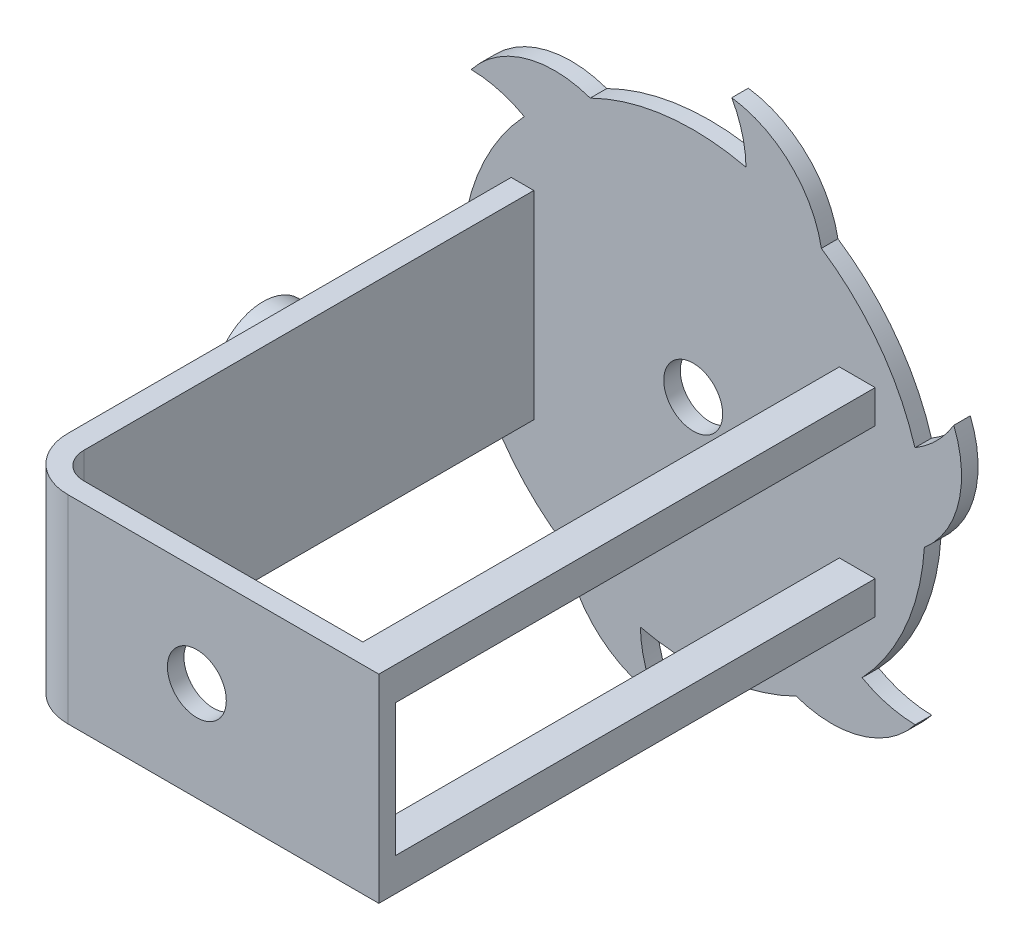
SolidWorks part; units mm, degrees
ref_plane "Front Plane" through (0, 0, 0) normal (0, 0, 1) x (1, 0, 0)
ref_plane "Top Plane" through (0, 0, 0) normal (0, 1, 0) x (1, 0, 0)
ref_plane "Right Plane" through (0, 0, 0) normal (1, 0, 0) x (0, 0, -1)
sketch "Sketch1" plane through (0, 0, 0) normal (0, 0, 1) x (1, 0, 0)
  line L0 (-873.9292, 0) -> (-35, 0) construction
  line L7 (0, -873.9292) -> (0, -35) construction
  line L8 (-618.4754, -618.4754) -> (-24.7487, -24.7487) construction
  line L9 (694.9078, -719.0993) -> (23.7269, -25.73) construction
  line L16 (0, 35) -> (0, 42822.5309) construction
  line L18 (35, 0) -> (42822.5309, 0) construction
  line L19 (-24.945, 24.5509) -> (-34080.9346, 35206.39) construction
  line L21 (24.7487, 24.7487) -> (30279.5878, 30279.5878) construction
  circle A0 centre (0, 0) radius 42.5 construction
  arc A1 (39.3732, 16) -> (33.5028, 10.1274) centre (24.779, 24.7184) cw
  arc A3 (39.3732, 16) -> (34.9308, -2.1991) centre (24.5504, 9.9765) cw
  arc A6 (33.543, -26.0982) -> (15.5609, -31.3506) centre (20.9151, -16.273) cw
  arc A7 (33.543, -26.0982) -> (25.522, -23.9505) centre (33.7963, -9.1001) cw
  arc A10 (-5.8302, -42.0982) -> (-19.3699, -29.1514) centre (-3.6353, -26.2495) cw
  arc A11 (-5.8302, -42.0982) -> (-7.9808, -34.078) centre (9.0172, -33.8185) cw
  arc A14 (-39.3732, -16) -> (-34.9308, 2.1991) centre (-24.5504, -9.9765) cw
  arc A15 (-39.3732, -16) -> (-33.5028, -10.1274) centre (-24.779, -24.7184) cw
  arc A18 (-33.543, 26.0982) -> (-15.5609, 31.3506) centre (-20.9151, 16.273) cw
  arc A19 (-33.543, 26.0982) -> (-25.522, 23.9505) centre (-33.7963, 9.1001) cw
  arc A22 (5.8302, 42.0982) -> (19.3699, 29.1514) centre (3.6353, 26.2495) cw
  arc A23 (5.8302, 42.0982) -> (7.9808, 34.078) centre (-9.0172, 33.8185) cw
  circle A25 centre (0, 0) radius 35
  point P16 (0, 0)
  point P73 (0, 0)
  dimension "D1" = 85
  dimension "D2" = 70
  dimension "D8" = 17
  dimension "D10" = 16
  dimension "D9" = 16
  dimension "D13" = 6
extrude "Boss-Extrude1" add sketch "Sketch1" along normal blind 2.5 contours A25 A14 A15 | A25 | A25 A18 A19 | A25 A22 A23 | A25 A3 A1 | A25 A6 A7 | A25 A10 A11
sketch "Sketch11" plane through (0, 0, 2.5) normal (0, 0, 1) x (1, 0, 0)
  circle A0 centre (0, 0) radius 4.45
  arc A18 (-33.5028, -10.1274) -> (-39.3732, -16) centre (-24.779, -24.7184) ccw
  arc A19 (-33.5028, -10.1274) -> (-19.3699, -29.1514) centre (0, 0) ccw
  arc A20 (-19.3699, -29.1514) -> (-5.8302, -42.0982) centre (-3.6353, -26.2495) ccw
  arc A21 (-7.9808, -34.078) -> (-5.8302, -42.0982) centre (9.0172, -33.8185) ccw
  arc A22 (-7.9808, -34.078) -> (15.5609, -31.3506) centre (0, 0) ccw
  arc A23 (15.5609, -31.3506) -> (33.543, -26.0982) centre (20.9151, -16.273) ccw
  arc A24 (25.522, -23.9505) -> (33.543, -26.0982) centre (33.7963, -9.1001) ccw
  arc A25 (25.522, -23.9505) -> (34.9308, -2.1991) centre (0, 0) ccw
  arc A26 (34.9308, -2.1991) -> (39.3732, 16) centre (24.5504, 9.9765) ccw
  arc A27 (33.5028, 10.1274) -> (39.3732, 16) centre (24.779, 24.7184) ccw
  arc A28 (33.5028, 10.1274) -> (19.3699, 29.1514) centre (0, 0) ccw
  arc A29 (19.3699, 29.1514) -> (5.8302, 42.0982) centre (3.6353, 26.2495) ccw
  arc A30 (7.9808, 34.078) -> (5.8302, 42.0982) centre (-9.0172, 33.8185) ccw
  arc A31 (7.9808, 34.078) -> (-15.5609, 31.3506) centre (0, 0) ccw
  arc A32 (-15.5609, 31.3506) -> (-33.543, 26.0982) centre (-20.9151, 16.273) ccw
  arc A33 (-25.522, 23.9505) -> (-33.543, 26.0982) centre (-33.7963, 9.1001) ccw
  arc A34 (-25.522, 23.9505) -> (-34.9308, 2.1991) centre (0, 0) ccw
  arc A35 (-34.9308, 2.1991) -> (-39.3732, -16) centre (-24.5504, -9.9765) ccw
  arc A36 (-33.5028, -10.1274) -> (-39.3732, -16) centre (-24.779, -24.7184) ccw
  arc A37 (-33.5028, -10.1274) -> (-19.3699, -29.1514) centre (0, 0) ccw
  arc A38 (-19.3699, -29.1514) -> (-5.8302, -42.0982) centre (-3.6353, -26.2495) ccw
  arc A39 (-7.9808, -34.078) -> (-5.8302, -42.0982) centre (9.0172, -33.8185) ccw
  arc A40 (-7.9808, -34.078) -> (15.5609, -31.3506) centre (0, 0) ccw
  arc A41 (15.5609, -31.3506) -> (33.543, -26.0982) centre (20.9151, -16.273) ccw
  arc A42 (25.522, -23.9505) -> (33.543, -26.0982) centre (33.7963, -9.1001) ccw
  arc A43 (25.522, -23.9505) -> (34.9308, -2.1991) centre (0, 0) ccw
  arc A44 (34.9308, -2.1991) -> (39.3732, 16) centre (24.5504, 9.9765) ccw
  arc A45 (33.5028, 10.1274) -> (39.3732, 16) centre (24.779, 24.7184) ccw
  arc A46 (33.5028, 10.1274) -> (19.3699, 29.1514) centre (0, 0) ccw
  arc A47 (19.3699, 29.1514) -> (5.8302, 42.0982) centre (3.6353, 26.2495) ccw
  arc A48 (7.9808, 34.078) -> (5.8302, 42.0982) centre (-9.0172, 33.8185) ccw
  arc A49 (7.9808, 34.078) -> (-15.5609, 31.3506) centre (0, 0) ccw
  arc A50 (-15.5609, 31.3506) -> (-33.543, 26.0982) centre (-20.9151, 16.273) ccw
  arc A51 (-25.522, 23.9505) -> (-33.543, 26.0982) centre (-33.7963, 9.1001) ccw
  arc A52 (-25.522, 23.9505) -> (-34.9308, 2.1991) centre (0, 0) ccw
  arc A53 (-34.9308, 2.1991) -> (-39.3732, -16) centre (-24.5504, -9.9765) ccw
  dimension "D2" = 8.9
  dimension "D1" = 0
extrude "Cut-Extrude5" cut sketch "Sketch11" against normal blind 10 contours A0
sketch "Sketch5" plane through (0, 0, 2.5) normal (0, 0, 1) x (1, 0, 0)
  line L1 (27.5, -15) -> (-27.5, -15)
  line L2 (27.5, -15) -> (27.5, 15)
  line L3 (27.5, 15) -> (-27.5, 15)
  line L4 (-27.5, -15) -> (-27.5, 15)
  line L5 (27.5, -15) -> (-27.5, 15) construction
  line L6 (27.5, 15) -> (-27.5, -15) construction
  arc A18 (-33.5028, -10.1274) -> (-39.3732, -16) centre (-24.779, -24.7184) ccw
  arc A19 (-33.5028, -10.1274) -> (-19.3699, -29.1514) centre (0, 0) ccw
  arc A20 (-19.3699, -29.1514) -> (-5.8302, -42.0982) centre (-3.6353, -26.2495) ccw
  arc A21 (-7.9808, -34.078) -> (-5.8302, -42.0982) centre (9.0172, -33.8185) ccw
  arc A22 (-7.9808, -34.078) -> (15.5609, -31.3506) centre (0, 0) ccw
  arc A23 (15.5609, -31.3506) -> (33.543, -26.0982) centre (20.9151, -16.273) ccw
  arc A24 (25.522, -23.9505) -> (33.543, -26.0982) centre (33.7963, -9.1001) ccw
  arc A25 (25.522, -23.9505) -> (34.9308, -2.1991) centre (0, 0) ccw
  arc A26 (34.9308, -2.1991) -> (39.3732, 16) centre (24.5504, 9.9765) ccw
  arc A27 (33.5028, 10.1274) -> (39.3732, 16) centre (24.779, 24.7184) ccw
  arc A28 (33.5028, 10.1274) -> (19.3699, 29.1514) centre (0, 0) ccw
  arc A29 (19.3699, 29.1514) -> (5.8302, 42.0982) centre (3.6353, 26.2495) ccw
  arc A30 (7.9808, 34.078) -> (5.8302, 42.0982) centre (-9.0172, 33.8185) ccw
  arc A31 (7.9808, 34.078) -> (-15.5609, 31.3506) centre (0, 0) ccw
  arc A32 (-15.5609, 31.3506) -> (-33.543, 26.0982) centre (-20.9151, 16.273) ccw
  arc A33 (-25.522, 23.9505) -> (-33.543, 26.0982) centre (-33.7963, 9.1001) ccw
  arc A34 (-25.522, 23.9505) -> (-34.9308, 2.1991) centre (0, 0) ccw
  arc A35 (-34.9308, 2.1991) -> (-39.3732, -16) centre (-24.5504, -9.9765) ccw
  arc A36 (-33.5028, -10.1274) -> (-39.3732, -16) centre (-24.779, -24.7184) ccw
  arc A37 (-33.5028, -10.1274) -> (-19.3699, -29.1514) centre (0, 0) ccw
  arc A38 (-19.3699, -29.1514) -> (-5.8302, -42.0982) centre (-3.6353, -26.2495) ccw
  arc A39 (-7.9808, -34.078) -> (-5.8302, -42.0982) centre (9.0172, -33.8185) ccw
  arc A40 (-7.9808, -34.078) -> (15.5609, -31.3506) centre (0, 0) ccw
  arc A41 (15.5609, -31.3506) -> (33.543, -26.0982) centre (20.9151, -16.273) ccw
  arc A42 (25.522, -23.9505) -> (33.543, -26.0982) centre (33.7963, -9.1001) ccw
  arc A43 (25.522, -23.9505) -> (34.9308, -2.1991) centre (0, 0) ccw
  arc A44 (34.9308, -2.1991) -> (39.3732, 16) centre (24.5504, 9.9765) ccw
  arc A45 (33.5028, 10.1274) -> (39.3732, 16) centre (24.779, 24.7184) ccw
  arc A46 (33.5028, 10.1274) -> (19.3699, 29.1514) centre (0, 0) ccw
  arc A47 (19.3699, 29.1514) -> (5.8302, 42.0982) centre (3.6353, 26.2495) ccw
  arc A48 (7.9808, 34.078) -> (5.8302, 42.0982) centre (-9.0172, 33.8185) ccw
  arc A49 (7.9808, 34.078) -> (-15.5609, 31.3506) centre (0, 0) ccw
  arc A50 (-15.5609, 31.3506) -> (-33.543, 26.0982) centre (-20.9151, 16.273) ccw
  arc A51 (-25.522, 23.9505) -> (-33.543, 26.0982) centre (-33.7963, 9.1001) ccw
  arc A52 (-25.522, 23.9505) -> (-34.9308, 2.1991) centre (0, 0) ccw
  arc A53 (-34.9308, 2.1991) -> (-39.3732, -16) centre (-24.5504, -9.9765) ccw
  dimension "D2" = 30
  dimension "D3" = 55
  dimension "D1" = 0
extrude "Boss-Extrude4" add sketch "Sketch5" along normal blind 75
sketch "Sketch6" plane through (27.5, 0, 0) normal (1, 0, 0) x (0, 0, -1)
  line L1 (-75, -10) -> (-2.5, -10)
  line L2 (-75, -10) -> (-75, 10)
  line L3 (-75, 10) -> (-2.5, 10)
  line L4 (-2.5, -15) -> (-2.5, 15)
  line L5 (-2.5, 15) -> (-77.5, 15)
  line L6 (-77.5, 15) -> (-77.5, -15)
  line L8 (-2.5, -15) -> (-2.5, 15)
  line L10 (-77.5, 15) -> (-77.5, -15)
  line L12 (-2.5, -10) -> (-2.5, 10)
  line L13 (-75, -10) -> (-2.5, 10) construction
  line L14 (-75, 10) -> (-2.5, -10) construction
  line L15 (-1000, 0) -> (49000, 0) construction
  line L18 (-2.5, 15) -> (-77.5, 15)
  line L20 (-77.5, -15) -> (-2.5, -15)
  line L21 (-77.5, -15) -> (-2.5, -15)
  point P2 (-38.75, 0)
  point P10 (0, 0)
  dimension "D2" = 20
  dimension "D4" = 2.5
  dimension "D5" = 0
  dimension "D1" = 0
extrude "Cut-Extrude2" cut sketch "Sketch6" against normal blind 45 contours L1 L12 L3 L2
sketch "Sketch7" plane through (-27.5, 0, 0) normal (-1, 0, 0) x (0, 0, 1)
  circle A0 centre (30, 0) radius 7.5
  dimension "D2" = 15
  dimension "D1" = 30
extrude "Boss-Extrude5" add sketch "Sketch7" along normal blind 10
sketch "Sketch8" plane through (0, -15, 0) normal (0, -1, 0) x (1, 0, 0)
  line L1 (-24.0827, 2.5) -> (22.0857, 2.5)
  line L2 (-24.0827, 2.5) -> (-24.0827, 70.5)
  line L3 (-20.0827, 74.5) -> (22.0857, 74.5)
  line L4 (-27.5, 2.5) -> (27.5, 2.5)
  line L5 (27.5, 2.5) -> (27.5, 77.5)
  line L6 (27.5, 77.5) -> (-27.5, 77.5)
  line L8 (-27.5, 2.5) -> (27.5, 2.5)
  line L10 (27.5, 77.5) -> (-27.5, 77.5)
  line L12 (22.0857, 2.5) -> (22.0857, 74.5)
  line L13 (-24.0827, 2.5) -> (22.0857, 74.5) construction
  line L14 (-24.0827, 74.5) -> (22.0857, 2.5) construction
  line L18 (27.5, 2.5) -> (27.5, 77.5)
  line L24 (-27.5, 77.5) -> (-27.5, 2.5)
  line L25 (-27.5, 77.5) -> (-27.5, 2.5)
  arc A0 (-24.0827, 70.5) -> (-20.0827, 74.5) centre (-20.0827, 70.5) cw
  point P2 (-0.9985, 38.5)
  dimension "D2" = 4
  dimension "D4" = 0
  dimension "D5" = 3
  dimension "D1" = 0
extrude "Cut-Extrude3" cut sketch "Sketch8" against normal blind 30 contours L1 L12 L3 L2
sketch "Sketch9" plane through (0, 0, 77.5) normal (0, 0, 1) x (1, 0, 0)
  line L1 (-6.7265, -7.5476) -> (-16.7265, -7.5476)
  line L2 (-6.7265, -7.5476) -> (-6.7265, 2.4524)
  line L3 (-6.7265, 2.4524) -> (-16.7265, 2.4524)
  line L4 (-27.5, 15) -> (-27.5, -15)
  line L5 (-27.5, -15) -> (27.5, -15)
  line L6 (27.5, -15) -> (27.5, 15)
  line L7 (27.5, 15) -> (-27.5, 15)
  line L8 (-27.5, 15) -> (-27.5, -15)
  line L9 (-27.5, -15) -> (27.5, -15)
  line L10 (27.5, -15) -> (27.5, 15)
  line L11 (27.5, 15) -> (-27.5, 15)
  line L12 (-16.7265, -7.5476) -> (-16.7265, 2.4524)
  line L13 (-6.7265, -7.5476) -> (-16.7265, 2.4524) construction
  line L14 (-6.7265, 2.4524) -> (-16.7265, -7.5476) construction
  point P2 (-11.7265, -2.5476)
  point P9 (-12, 0)
  point P11 (-11.7265, -2.5476)
  dimension "D2" = 12
  dimension "D3" = 10
  dimension "D4" = 10
  dimension "D1" = 0
fillet "Fillet1" radius 8 1 edges at (-27.5, 0, 77.5)
